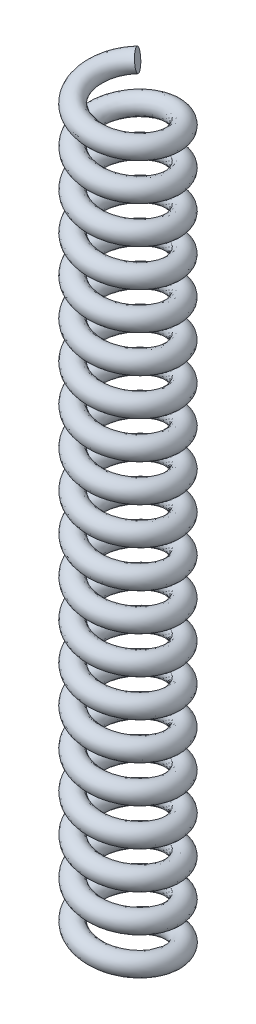
SolidWorks part; units mm, degrees
material "AISI 304"
ref_plane "Front Plane" through (0, 0, 0) normal (0, 0, 1) x (1, 0, 0)
ref_plane "Top Plane" through (0, 0, 0) normal (0, 1, 0) x (1, 0, 0)
ref_plane "Right Plane" through (0, 0, 0) normal (1, 0, 0) x (0, 0, -1)
sketch "Sketch8" plane through (0, 0, 0) normal (0, 1, 0) x (1, 0, 0)
  circle A0 centre (0, 0) radius 10
  dimension "D1" = 20
curve "Helix/Spiral2" pitch 9.5 height 190 turns 20
ref_plane "Plane2" through (-5.7358, 190, -8.1915) normal (0.8099, 0.1495, -0.5671) x (0.3451, 0.6603, 0.667)
sketch "Sketch9" plane through (-5.7358, 190, -8.1915) normal (0.8099, 0.1495, -0.5671) x (0.3451, 0.6603, 0.667)
  circle A0 centre (0, 0) radius 2.5
  dimension "D1" = 5
sweep "Sweep7" add profiles "Sketch9" path "Helix/Spiral2"
